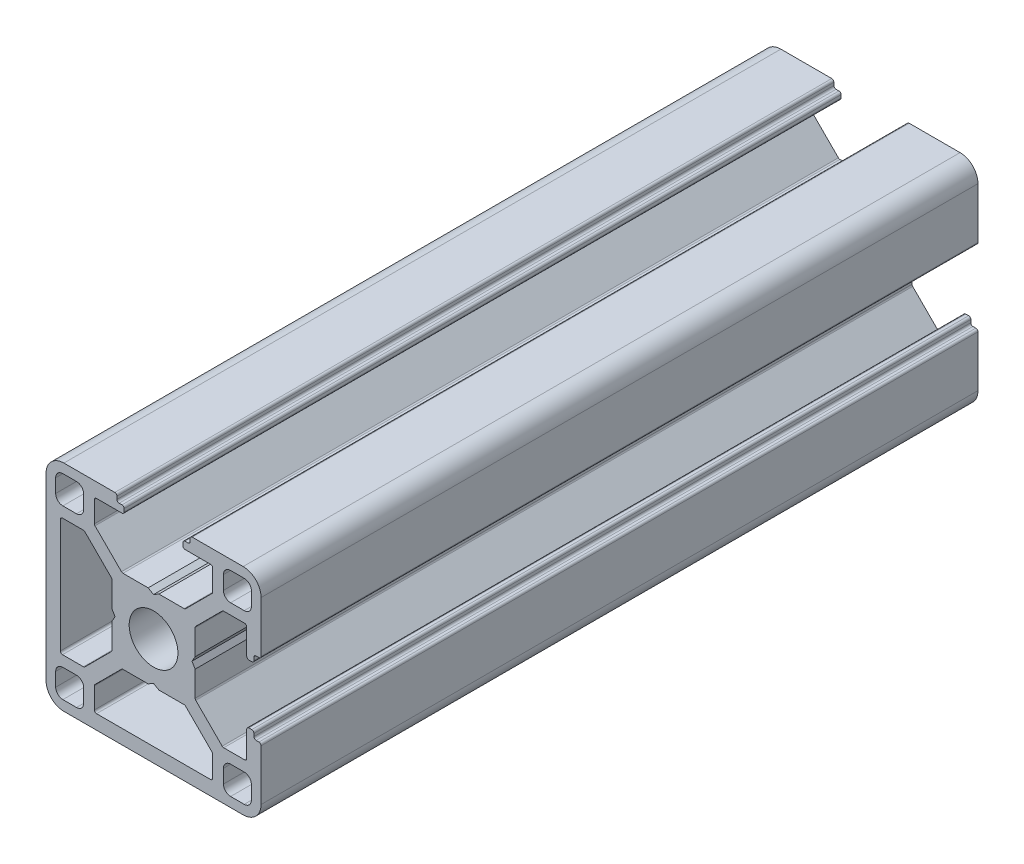
SolidWorks part; units mm, degrees
ref_plane "前视基准面" through (0, 0, 0) normal (0, 0, 1) x (1, 0, 0)
ref_plane "上视基准面" through (0, 0, 0) normal (0, 1, 0) x (1, 0, 0)
ref_plane "右视基准面" through (0, 0, 0) normal (1, 0, 0) x (0, 0, -1)
sketch "草图1" plane through (0, 0, 0) normal (0, 0, 1) x (1, 0, 0)
  line L0 (5.8596, 16.0341) -> (12.9596, 16.0341)
  line L1 (15.4596, 13.5341) -> (15.4596, 6.4341)
  line L2 (15.1596, 6.1341) -> (14.7596, 6.1341)
  line L3 (14.4596, 5.8341) -> (14.4596, 5.4341)
  line L4 (14.1596, 5.1341) -> (13.7596, 5.1341)
  line L5 (13.4596, 5.4341) -> (13.4596, 8.9841)
  line L6 (13.1596, 9.2841) -> (10.2481, 9.2841)
  line L7 (10.036, 9.1963) -> (6.3475, 5.5078)
  line L8 (6.2596, 5.2957) -> (6.2596, 1.7841)
  line L9 (6.2596, 1.7841) -> (5.8266, 1.0341)
  line L10 (5.8266, 1.0341) -> (6.2596, 0.2841)
  line L11 (6.2596, 0.2841) -> (6.2596, -3.2274)
  line L12 (6.3475, -3.4395) -> (10.036, -7.128)
  line L13 (10.2481, -7.2159) -> (13.1596, -7.2159)
  line L14 (13.4596, -6.9159) -> (13.4596, -3.3659)
  line L15 (13.7596, -3.0659) -> (14.1596, -3.0659)
  line L16 (14.4596, -3.3659) -> (14.4596, -3.7659)
  line L17 (14.7596, -4.0659) -> (15.1596, -4.0659)
  line L18 (15.4596, -4.3659) -> (15.4596, -11.4659)
  line L19 (12.9596, -13.9659) -> (-12.0404, -13.9659)
  line L20 (-14.5404, -11.4659) -> (-14.5404, 13.5341)
  line L21 (-12.0404, 16.0341) -> (-4.9404, 16.0341)
  line L22 (-4.6404, 15.7341) -> (-4.6404, 15.3341)
  line L23 (-4.3404, 15.0341) -> (-3.9404, 15.0341)
  line L24 (-3.6404, 14.7341) -> (-3.6404, 14.3341)
  line L25 (-3.9404, 14.0341) -> (-7.4904, 14.0341)
  line L26 (-7.7904, 13.7341) -> (-7.7904, 10.8226)
  line L27 (-7.7025, 10.6105) -> (-4.014, 6.922)
  line L28 (-3.8019, 6.8341) -> (-0.2904, 6.8341)
  line L29 (-0.2904, 6.8341) -> (0.4596, 6.4011)
  line L30 (0.4596, 6.4011) -> (1.2096, 6.8341)
  line L31 (1.2096, 6.8341) -> (4.7211, 6.8341)
  line L32 (4.9333, 6.922) -> (8.6217, 10.6105)
  line L33 (8.7096, 10.8226) -> (8.7096, 13.7341)
  line L34 (8.4096, 14.0341) -> (4.8596, 14.0341)
  line L35 (4.5596, 14.3341) -> (4.5596, 14.7341)
  line L36 (4.8596, 15.0341) -> (5.2596, 15.0341)
  line L37 (5.5596, 15.3341) -> (5.5596, 15.7341)
  line L38 (8.4096, -11.9659) -> (-7.4904, -11.9659)
  line L39 (-7.7904, -11.6659) -> (-7.7904, -8.7543)
  line L40 (8.7096, -8.7543) -> (8.7096, -11.6659)
  line L41 (-7.7025, -8.5422) -> (-4.014, -4.8537)
  line L42 (4.9333, -4.8537) -> (8.6217, -8.5422)
  line L43 (-3.8019, -4.7659) -> (-0.2904, -4.7659)
  line L44 (1.2096, -4.7659) -> (4.7211, -4.7659)
  line L45 (0.4596, -4.3328) -> (-0.2904, -4.7659)
  line L46 (1.2096, -4.7659) -> (0.4596, -4.3328)
  line L47 (-10.2904, -8.7159) -> (-12.1904, -8.7159)
  line L48 (-13.1904, -9.7159) -> (-13.1904, -11.6159)
  line L49 (-12.1904, -12.6159) -> (-10.2904, -12.6159)
  line L50 (-9.2904, -11.6159) -> (-9.2904, -9.7159)
  line L51 (-9.2904, 13.6841) -> (-9.2904, 11.7841)
  line L52 (-10.2904, 10.7841) -> (-12.1904, 10.7841)
  line L53 (-13.1904, 11.7841) -> (-13.1904, 13.6841)
  line L54 (-12.1904, 14.6841) -> (-10.2904, 14.6841)
  line L55 (13.1096, 10.7841) -> (11.2096, 10.7841)
  line L56 (10.2096, 11.7841) -> (10.2096, 13.6841)
  line L57 (11.2096, 14.6841) -> (13.1096, 14.6841)
  line L58 (14.1096, 13.6841) -> (14.1096, 11.7841)
  line L59 (-5.3404, 5.2957) -> (-5.3404, 1.7841)
  line L60 (-5.3404, 1.7841) -> (-4.9074, 1.0341)
  line L61 (-4.9074, 1.0341) -> (-5.3404, 0.2841)
  line L62 (-5.3404, 0.2841) -> (-5.3404, -3.2274)
  line L63 (-5.4283, -3.4395) -> (-9.1167, -7.128)
  line L64 (-9.3289, -7.2159) -> (-12.2404, -7.2159)
  line L65 (-12.5404, -6.9159) -> (-12.5404, 8.9841)
  line L66 (-12.2404, 9.2841) -> (-9.3289, 9.2841)
  line L67 (-9.1167, 9.1963) -> (-5.4283, 5.5078)
  line L68 (14.1096, -11.6159) -> (14.1096, -9.7159)
  line L69 (13.1096, -8.7159) -> (11.2096, -8.7159)
  line L70 (10.2096, -9.7159) -> (10.2096, -11.6159)
  line L71 (11.2096, -12.6159) -> (13.1096, -12.6159)
  circle A0 centre (0.4596, 1.0341) radius 3.4
  arc A1 (15.4596, 13.5341) -> (12.9596, 16.0341) centre (12.9596, 13.5341) ccw
  arc A2 (15.1596, 6.1341) -> (15.4596, 6.4341) centre (15.1596, 6.4341) ccw
  arc A3 (14.7596, 6.1341) -> (14.4596, 5.8341) centre (14.7596, 5.8341) ccw
  arc A4 (14.1596, 5.1341) -> (14.4596, 5.4341) centre (14.1596, 5.4341) ccw
  arc A5 (13.4596, 5.4341) -> (13.7596, 5.1341) centre (13.7596, 5.4341) ccw
  arc A6 (13.4596, 8.9841) -> (13.1596, 9.2841) centre (13.1596, 8.9841) ccw
  arc A7 (10.2481, 9.2841) -> (10.036, 9.1963) centre (10.2481, 8.9841) ccw
  arc A8 (6.3475, 5.5078) -> (6.2596, 5.2957) centre (6.5596, 5.2957) ccw
  arc A9 (6.2596, -3.2274) -> (6.3475, -3.4395) centre (6.5596, -3.2274) ccw
  arc A10 (10.036, -7.128) -> (10.2481, -7.2159) centre (10.2481, -6.9159) ccw
  arc A11 (13.1596, -7.2159) -> (13.4596, -6.9159) centre (13.1596, -6.9159) ccw
  arc A12 (13.7596, -3.0659) -> (13.4596, -3.3659) centre (13.7596, -3.3659) ccw
  arc A13 (14.4596, -3.3659) -> (14.1596, -3.0659) centre (14.1596, -3.3659) ccw
  arc A14 (14.4596, -3.7659) -> (14.7596, -4.0659) centre (14.7596, -3.7659) ccw
  arc A15 (15.4596, -4.3659) -> (15.1596, -4.0659) centre (15.1596, -4.3659) ccw
  arc A16 (12.9596, -13.9659) -> (15.4596, -11.4659) centre (12.9596, -11.4659) ccw
  arc A17 (-14.5404, -11.4659) -> (-12.0404, -13.9659) centre (-12.0404, -11.4659) ccw
  arc A18 (-12.0404, 16.0341) -> (-14.5404, 13.5341) centre (-12.0404, 13.5341) ccw
  arc A19 (-4.6404, 15.7341) -> (-4.9404, 16.0341) centre (-4.9404, 15.7341) ccw
  arc A20 (-4.6404, 15.3341) -> (-4.3404, 15.0341) centre (-4.3404, 15.3341) ccw
  arc A21 (-3.6404, 14.7341) -> (-3.9404, 15.0341) centre (-3.9404, 14.7341) ccw
  arc A22 (-3.9404, 14.0341) -> (-3.6404, 14.3341) centre (-3.9404, 14.3341) ccw
  arc A23 (-7.4904, 14.0341) -> (-7.7904, 13.7341) centre (-7.4904, 13.7341) ccw
  arc A24 (-7.7904, 10.8226) -> (-7.7025, 10.6105) centre (-7.4904, 10.8226) ccw
  arc A25 (-4.014, 6.922) -> (-3.8019, 6.8341) centre (-3.8019, 7.1341) ccw
  arc A26 (4.7211, 6.8341) -> (4.9333, 6.922) centre (4.7211, 7.1341) ccw
  arc A27 (8.6217, 10.6105) -> (8.7096, 10.8226) centre (8.4096, 10.8226) ccw
  arc A28 (8.7096, 13.7341) -> (8.4096, 14.0341) centre (8.4096, 13.7341) ccw
  arc A29 (4.5596, 14.3341) -> (4.8596, 14.0341) centre (4.8596, 14.3341) ccw
  arc A30 (4.8596, 15.0341) -> (4.5596, 14.7341) centre (4.8596, 14.7341) ccw
  arc A31 (5.2596, 15.0341) -> (5.5596, 15.3341) centre (5.2596, 15.3341) ccw
  arc A32 (5.8596, 16.0341) -> (5.5596, 15.7341) centre (5.8596, 15.7341) ccw
  arc A33 (-7.7904, -11.6659) -> (-7.4904, -11.9659) centre (-7.4904, -11.6659) ccw
  arc A34 (8.4096, -11.9659) -> (8.7096, -11.6659) centre (8.4096, -11.6659) ccw
  arc A35 (-7.7025, -8.5422) -> (-7.7904, -8.7543) centre (-7.4904, -8.7543) ccw
  arc A36 (8.7096, -8.7543) -> (8.6217, -8.5422) centre (8.4096, -8.7543) ccw
  arc A37 (-3.8019, -4.7659) -> (-4.014, -4.8537) centre (-3.8019, -5.0659) ccw
  arc A38 (4.9333, -4.8537) -> (4.7211, -4.7659) centre (4.7211, -5.0659) ccw
  arc A39 (-9.2904, -9.7159) -> (-10.2904, -8.7159) centre (-10.2904, -9.7159) ccw
  arc A40 (-12.1904, -8.7159) -> (-13.1904, -9.7159) centre (-12.1904, -9.7159) ccw
  arc A41 (-13.1904, -11.6159) -> (-12.1904, -12.6159) centre (-12.1904, -11.6159) ccw
  arc A42 (-10.2904, -12.6159) -> (-9.2904, -11.6159) centre (-10.2904, -11.6159) ccw
  arc A43 (-10.2904, 10.7841) -> (-9.2904, 11.7841) centre (-10.2904, 11.7841) ccw
  arc A44 (-13.1904, 11.7841) -> (-12.1904, 10.7841) centre (-12.1904, 11.7841) ccw
  arc A45 (-12.1904, 14.6841) -> (-13.1904, 13.6841) centre (-12.1904, 13.6841) ccw
  arc A46 (-9.2904, 13.6841) -> (-10.2904, 14.6841) centre (-10.2904, 13.6841) ccw
  arc A47 (10.2096, 11.7841) -> (11.2096, 10.7841) centre (11.2096, 11.7841) ccw
  arc A48 (11.2096, 14.6841) -> (10.2096, 13.6841) centre (11.2096, 13.6841) ccw
  arc A49 (14.1096, 13.6841) -> (13.1096, 14.6841) centre (13.1096, 13.6841) ccw
  arc A50 (13.1096, 10.7841) -> (14.1096, 11.7841) centre (13.1096, 11.7841) ccw
  arc A51 (-5.4283, -3.4395) -> (-5.3404, -3.2274) centre (-5.6404, -3.2274) ccw
  arc A52 (-9.3289, -7.2159) -> (-9.1167, -7.128) centre (-9.3289, -6.9159) ccw
  arc A53 (-12.5404, -6.9159) -> (-12.2404, -7.2159) centre (-12.2404, -6.9159) ccw
  arc A54 (-12.2404, 9.2841) -> (-12.5404, 8.9841) centre (-12.2404, 8.9841) ccw
  arc A55 (-9.1167, 9.1963) -> (-9.3289, 9.2841) centre (-9.3289, 8.9841) ccw
  arc A56 (-5.3404, 5.2957) -> (-5.4283, 5.5078) centre (-5.6404, 5.2957) ccw
  arc A57 (13.1096, -12.6159) -> (14.1096, -11.6159) centre (13.1096, -11.6159) ccw
  arc A58 (14.1096, -9.7159) -> (13.1096, -8.7159) centre (13.1096, -9.7159) ccw
  arc A59 (11.2096, -8.7159) -> (10.2096, -9.7159) centre (11.2096, -9.7159) ccw
  arc A60 (10.2096, -11.6159) -> (11.2096, -12.6159) centre (11.2096, -11.6159) ccw
extrude "凸台-拉伸1" add sketch "草图1" along normal blind 100
